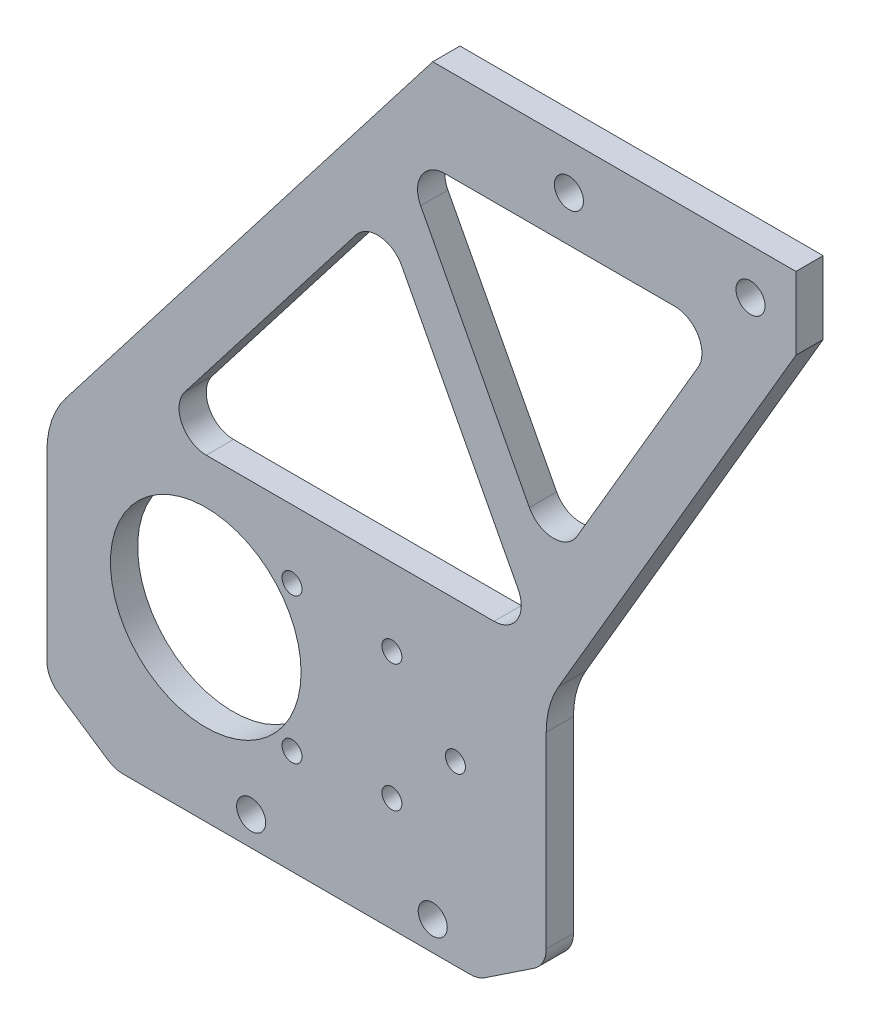
SolidWorks part; units mm, degrees
material "Thornel Mat VMA"
ref_plane "前视基准面" through (0, 0, 0) normal (0, 0, 1) x (1, 0, 0)
ref_plane "上视基准面" through (0, 0, 0) normal (0, 1, 0) x (1, 0, 0)
ref_plane "右视基准面" through (0, 0, 0) normal (1, 0, 0) x (0, 0, -1)
sketch "草图5" plane through (0, 0, 0) normal (0, 0, 1) x (1, 0, 0)
  line L0 (-62.5, -55) -> (-7.5, -55) construction
  line L1 (-20, 0) -> (20, 0)
  line L3 (-7.5, -55) -> (-7.5, -80)
  line L4 (-7.5, -80) -> (-15, -85)
  line L5 (-15, -85) -> (-55, -85)
  line L6 (-62.5, -80) -> (-55, -85)
  line L7 (-62.5, -55) -> (-62.5, -80)
  line L8 (-20, 0) -> (-62.5, -55)
  line L9 (-62.5, -80) -> (-7.5, -80) construction
  line L10 (-35, -80) -> (-35, -85) construction
  line L11 (20, 0) -> (20, -8)
  line L12 (20, -8) -> (-7.5, -55)
  point P0 (0, 0)
  dimension "D1" = 55
  dimension "D2" = 40
  dimension "D3" = 5
  dimension "D4" = 25
  dimension "D5" = 55
  dimension "D6" = 40
  dimension "D7" = 8
  dimension "D8" = 35
extrude "凸台-拉伸3" add sketch "草图5" along normal blind 3
sketch "草图6" plane through (0, 0, 3) normal (0, 0, 1) x (1, 0, 0)
  line L0 (-5, -5) -> (15, -5) construction
  line L1 (20, 0) -> (-20, 0) construction
  line L2 (-62.5, -67.5) -> (-7.5, -67.5) construction
  line L3 (-55, -85) -> (-15, -85) construction
  line L4 (-40, -81.8) -> (-20, -81.8) construction
  line L9 (-55, -65.5) -> (-15, -65.5) construction
  line L10 (-55, -75.5) -> (-15, -75.5) construction
  line L19 (-62.5, -55) -> (-62.5, -80) construction
  line L20 (-7.5, -80) -> (-7.5, -55) construction
  line L21 (-35, -67.5) -> (-35, 49932.5) construction
  line L22 (-55, -75.5) -> (-55, -55.5) construction
  line L23 (-55, -55.5) -> (-15, -55.5) construction
  line L24 (-15, -75.5) -> (-15, -55.5) construction
  line L25 (-55, -75.5) -> (-15, -55.5) construction
  line L26 (-55, -55.5) -> (-15, -75.5) construction
  circle A0 centre (-5, -5) radius 1.6
  circle A1 centre (15, -5) radius 1.6
  circle A6 centre (-40, -81.8) radius 1.6
  circle A7 centre (-20, -81.8) radius 1.6
  circle A8 centre (-17.5, -65.5) radius 1.1
  circle A9 centre (-24.5, -58.5) radius 1.1
  circle A10 centre (-35.5, -57.5) radius 1.1
  circle A11 centre (-35.5, -73.5) radius 1.1
  circle A12 centre (-24.5, -72.5) radius 1.1
  circle A13 centre (-45, -65.5) radius 10.5
  point P12 (-35, -65.5)
  point P20 (-35, -67.5)
  dimension "D1" = 3.2
  dimension "D4" = 5
  dimension "D7" = 40
  dimension "D11" = 8
  dimension "D13" = 3.2
  dimension "D14" = 5
  dimension "D15" = 3.2
  dimension "D16" = 3.2
  dimension "D5" = 3.2
  dimension "D8" = 2.2
  dimension "D20" = 21
  dimension "D2" = 5
  dimension "D3" = 20
  dimension "D6" = 20
  dimension "D9" = 9.5
  dimension "D10" = 7
  dimension "D12" = 20
  dimension "D17" = 20.5
  dimension "D18" = 2.5
  dimension "D19" = 2
  dimension "D21" = 30
extrude "切除-拉伸1" cut sketch "草图6" against normal through all
sketch "草图7" plane through (0, 0, 3) normal (0, 0, 1) x (1, 0, 0)
  line L0 (-28.4432, -20.7393) -> (-47.3181, -45.1657)
  line L1 (-44.9443, -50) -> (-13.2465, -50)
  line L2 (-4.1088, -37.3233) -> (9.2364, -14.515)
  line L3 (6.6471, -10) -> (-18.6716, -10)
  line L4 (-55, -85) -> (-15, -85) construction
  line L5 (-20, 0) -> (-62.5, -55) construction
  line L6 (-7.5, -55) -> (20, -8) construction
  line L8 (20, 0) -> (-20, 0) construction
  line L10 (-23.4131, -21.1792) -> (-10.5903, -45.6056)
  line L11 (-21.3278, -14.3944) -> (-9.3544, -37.2027)
  arc A0 (9.2364, -14.515) -> (6.6471, -10) centre (6.6471, -13) ccw
  arc A1 (-21.3278, -14.3944) -> (-18.6716, -10) centre (-18.6716, -13) cw
  arc A2 (-9.3544, -37.2027) -> (-4.1088, -37.3233) centre (-6.6982, -35.8082) ccw
  arc A3 (-10.5903, -45.6056) -> (-13.2465, -50) centre (-13.2465, -47) cw
  arc A4 (-47.3181, -45.1657) -> (-44.9443, -50) centre (-44.9443, -47) ccw
  arc A5 (-23.4131, -21.1792) -> (-28.4432, -20.7393) centre (-26.0694, -22.5736) ccw
  dimension "D7" = 3
  dimension "D1" = 6
  dimension "D2" = 6
  dimension "D3" = 35
  dimension "D4" = 10
  dimension "D8" = 5
extrude "切除-拉伸2" cut sketch "草图7" against normal blind 10
fillet "圆角1" radius 10 2 edges at (-62.5, -55, 1.5) (-7.5, -55, 1.5)
fillet "圆角2" radius 3 4 edges at (-7.5, -80, 1.5) (-15, -85, 1.5) (-55, -85, 1.5) (-62.5, -80, 1.5)
equation "\"3。2\"=3.48292"
equation "\"7。5\"=5"
